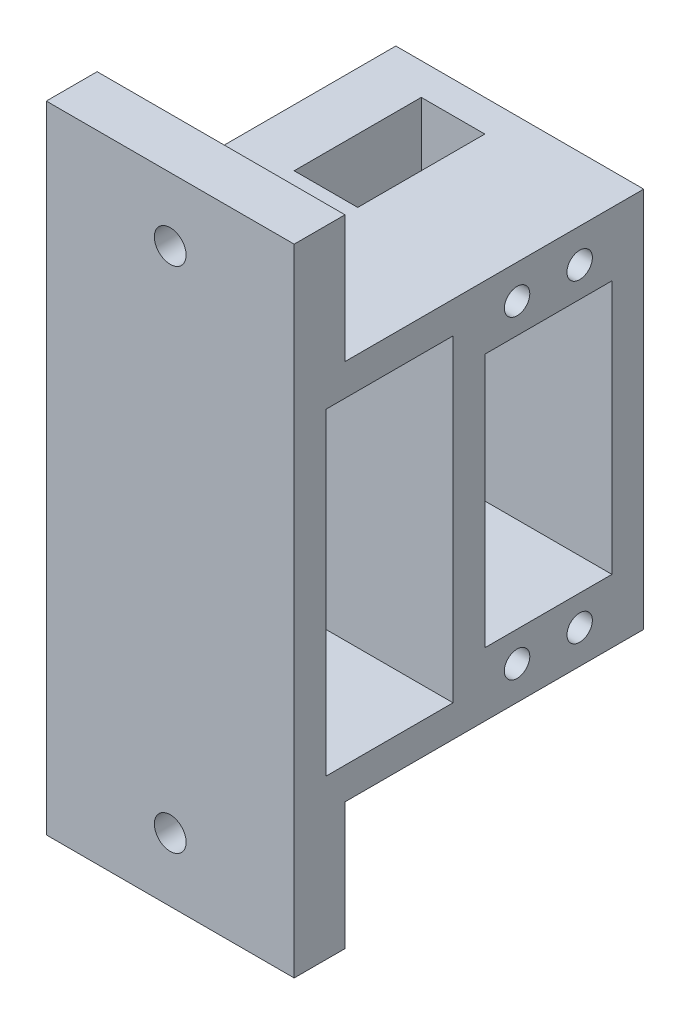
SolidWorks part; units mm, degrees
material "ABS"
ref_plane "Front Plane" through (0, 0, 0) normal (0, 0, 1) x (1, 0, 0)
ref_plane "Top Plane" through (0, 0, 0) normal (0, 1, 0) x (1, 0, 0)
ref_plane "Right Plane" through (0, 0, 0) normal (1, 0, 0) x (0, 0, -1)
sketch "Sketch1" plane through (0, 0, 0) normal (1, 0, 0) x (0, 0, -1)
  line L1 (-15, 30) -> (15, 30)
  line L2 (-15, 30) -> (-15, -30)
  line L3 (-15, -30) -> (15, -30)
  line L4 (15, 30) -> (15, -30)
  line L5 (-15, 30) -> (15, -30) construction
  line L6 (-15, -30) -> (15, 30) construction
  point P0 (0, 0)
  dimension "D1" = 60
  dimension "D2" = 30
extrude "Boss-Extrude1" add sketch "Sketch1" along normal blind 39
sketch "Sketch2" plane through (39, 0, 0) normal (1, 0, 0) x (0, 0, -1)
  line L1 (-10, 20) -> (10, 20)
  line L2 (-10, 20) -> (-10, -20)
  line L3 (-10, -20) -> (10, -20)
  line L4 (10, 20) -> (10, -20)
  line L5 (-10, 20) -> (10, -20) construction
  line L6 (-10, -20) -> (10, 20) construction
  point P0 (0, 0)
  dimension "D1" = 20
  dimension "D2" = 40
extrude "Cut-Extrude1" cut sketch "Sketch2" against normal blind 30
sketch "Sketch3" plane through (39, 0, 0) normal (1, 0, 0) x (0, 0, -1)
  line L0 (10, 20) -> (-10, 20) construction
  line L1 (15, 30) -> (-15, 30) construction
  line L2 (0, 0) -> (15, 0) construction
  line L3 (15, -30) -> (15, 30) construction
  circle A0 centre (-4.925, 24.71) radius 2
  circle A1 centre (4.925, 24.71) radius 2
  circle A2 centre (4.925, -24.71) radius 2
  circle A3 centre (-4.925, -24.71) radius 2
  point P6 (0, 20)
  dimension "D1" = 4
  dimension "D2" = 4
  dimension "D3" = 9.85
  dimension "D4" = 4.925
  dimension "D5" = 5.29
extrude "Cut-Extrude2" cut sketch "Sketch3" against normal blind 20
sketch "Sketch4" plane through (0, 20, 0) normal (0, -1, 0) x (1, 0, 0)
  line L0 (9, -10) -> (39, -10) construction
  line L1 (9, 10) -> (19, 10)
  line L2 (9, 10) -> (9, -10)
  line L3 (9, -10) -> (19, -10)
  line L4 (19, 10) -> (19, -10)
  dimension "D1" = 10
extrude "Cut-Extrude3" cut sketch "Sketch4" against normal up to surface (10 mm away) up to face at (19.5, 30, 0)
sketch "Sketch5" plane through (0, 0, 15) normal (0, 0, 1) x (1, 0, 0)
  line L1 (0, 30) -> (39, 30)
  line L2 (0, 30) -> (0, -30)
  line L3 (0, -30) -> (39, -30)
  line L4 (39, 30) -> (39, -30)
extrude "Boss-Extrude2" add sketch "Sketch5" along normal blind 25
sketch "Sketch6" plane through (39, 0, 0) normal (1, 0, 0) x (0, 0, -1)
  line L0 (15, 30) -> (-40, 30) construction
  line L1 (-35, 25) -> (-15, 25)
  line L2 (-35, 25) -> (-35, -25)
  line L3 (-35, -25) -> (-15, -25)
  line L4 (-15, 25) -> (-15, -25)
  line L5 (-40, -30) -> (15, -30) construction
  line L6 (-40, -30) -> (-40, 30) construction
  line L7 (-10, 20) -> (-10, -20) construction
  dimension "D1" = 5
  dimension "D2" = 5
  dimension "D3" = 5
  dimension "D4" = 5
extrude "Cut-Extrude4" cut sketch "Sketch6" against normal up to surface (39 mm away) up to face at (0, 0, 12.5)
sketch "Sketch7" plane through (0, -30, 0) normal (0, -1, 0) x (-1, 0, 0)
  line L0 (-39, -40) -> (-39, 15) construction
  line L1 (-39, -32) -> (0, -32)
  line L2 (-39, -32) -> (-39, -40)
  line L3 (-39, -40) -> (0, -40)
  line L4 (0, -32) -> (0, -40)
  dimension "D1" = 8
extrude "Boss-Extrude3" add sketch "Sketch7" along normal blind 20
sketch "Sketch8" plane through (0, 30, 0) normal (0, 1, 0) x (1, 0, 0)
  line L0 (0, 15) -> (0, -40) construction
  line L1 (39, -40) -> (0, -40)
  line L2 (39, -40) -> (39, -32)
  line L3 (39, -32) -> (0, -32)
  line L4 (0, -40) -> (0, -32)
  dimension "D1" = 8
extrude "Boss-Extrude4" add sketch "Sketch8" along normal blind 20
sketch "Sketch9" plane through (0, 0, 32) normal (0, 0, -1) x (-1, 0, 0)
  line L0 (-39, 50) -> (0, 50) construction
  line L1 (0, 50) -> (0, 30) construction
  line L2 (0, -50) -> (0, -30) construction
  line L3 (0, -50) -> (-39, -50) construction
  circle A0 centre (-19.5, -40) radius 2.5
  circle A1 centre (-19.5, 40) radius 2.5
  dimension "D1" = 5
  dimension "D2" = 5
  dimension "D3" = 10
  dimension "D4" = 19.5
  dimension "D5" = 19.5
  dimension "D6" = 10
extrude "Cut-Extrude5" cut sketch "Sketch9" against normal up to surface (8 mm away) up to face at (19.5, 0, 40)
